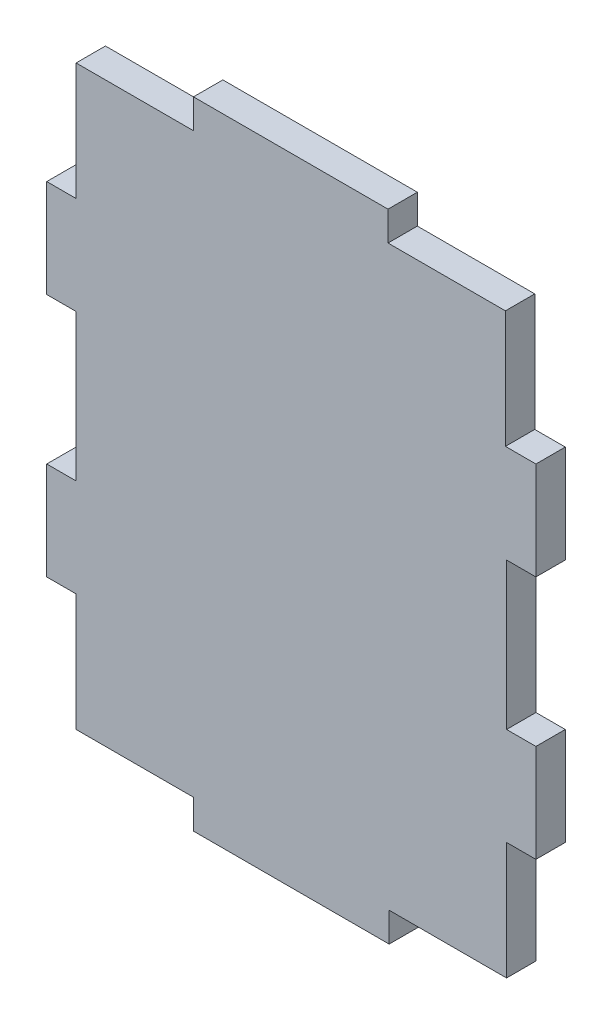
SolidWorks part; units mm, degrees
ref_plane "Plan de face" through (0, 0, 0) normal (0, 0, 1) x (1, 0, 0)
ref_plane "Plan de dessus" through (0, 0, 0) normal (0, 1, 0) x (1, 0, 0)
ref_plane "Plan de droite" through (0, 0, 0) normal (1, 0, 0) x (0, 0, -1)
sketch "Esquisse1" plane through (0, 0, 0) normal (0, 0, 1) x (1, 0, 0)
  line L1 (0, 0) -> (-100, 0)
  line L2 (0, 0) -> (0, 130)
  line L3 (0, 130) -> (-100, 130)
  line L4 (-100, 0) -> (-100, 130)
  dimension "D1" = 100
  dimension "D2" = 130
extrude "Boss.-Extru.1" add sketch "Esquisse1" along normal blind 6
sketch "Esquisse2" plane through (0, 0, 6) normal (0, 0, 1) x (1, 0, 0)
  line L0 (-100, 130) -> (-100, 0) construction
  line L1 (-100, 130) -> (-70, 130)
  line L2 (-100, 130) -> (-100, 100)
  line L3 (-94, 124) -> (-70, 124)
  line L4 (-70, 130) -> (-70, 124)
  line L5 (0, 130) -> (-30.2355, 130)
  line L6 (0, 130) -> (0, 100)
  line L7 (-6.2355, 124) -> (-30.2355, 124)
  line L8 (-30.2355, 130) -> (-30.2355, 124)
  line L9 (-100, 0) -> (-70, 0)
  line L10 (-100, 30) -> (-100, 0)
  line L11 (-94, 6) -> (-70, 6)
  line L12 (-70, 0) -> (-70, 6)
  line L13 (0, 0) -> (-30, 0)
  line L14 (0, 0) -> (0, 30)
  line L15 (-6, 6) -> (-30, 6)
  line L16 (-30, 0) -> (-30, 6)
  line L19 (-100, 100) -> (-94, 100)
  line L20 (-94, 124) -> (-94, 100)
  line L23 (-100, 30) -> (-94, 30)
  line L24 (-94, 6) -> (-94, 30)
  line L25 (-100, 50) -> (-94, 50)
  line L26 (-100, 50) -> (-100, 80)
  line L27 (-100, 80) -> (-94, 80)
  line L28 (-94, 50) -> (-94, 80)
  line L29 (0, 0) -> (0, 130) construction
  line L32 (0, 100) -> (-6.2355, 100)
  line L33 (-6.2355, 124) -> (-6.2355, 100)
  line L34 (0, 80) -> (-6, 80)
  line L35 (0, 80) -> (0, 50)
  line L36 (0, 50) -> (-6, 50)
  line L37 (-6, 80) -> (-6, 50)
  line L41 (0, 30) -> (-6, 30)
  line L42 (-6, 6) -> (-6, 30)
  dimension "D2" = 6
  dimension "D3" = 6
  dimension "D4" = 30
  dimension "D5" = 30
  dimension "D6" = 6
  dimension "D7" = 6
  dimension "D8" = 30
  dimension "D9" = 30
  dimension "D10" = 24
  dimension "D11" = 6
  dimension "D12" = 6
  dimension "D13" = 6
  dimension "D14" = 24
  dimension "D15" = 20
  dimension "D16" = 6.2355
  dimension "D17" = 24
  dimension "D18" = 30
  dimension "D19" = 24
  dimension "D20" = 6
  dimension "D21" = 30
  dimension "D22" = 6
  dimension "D23" = 20
extrude "Enlèv. mat.-Extru.1" cut sketch "Esquisse2" against normal blind 6
